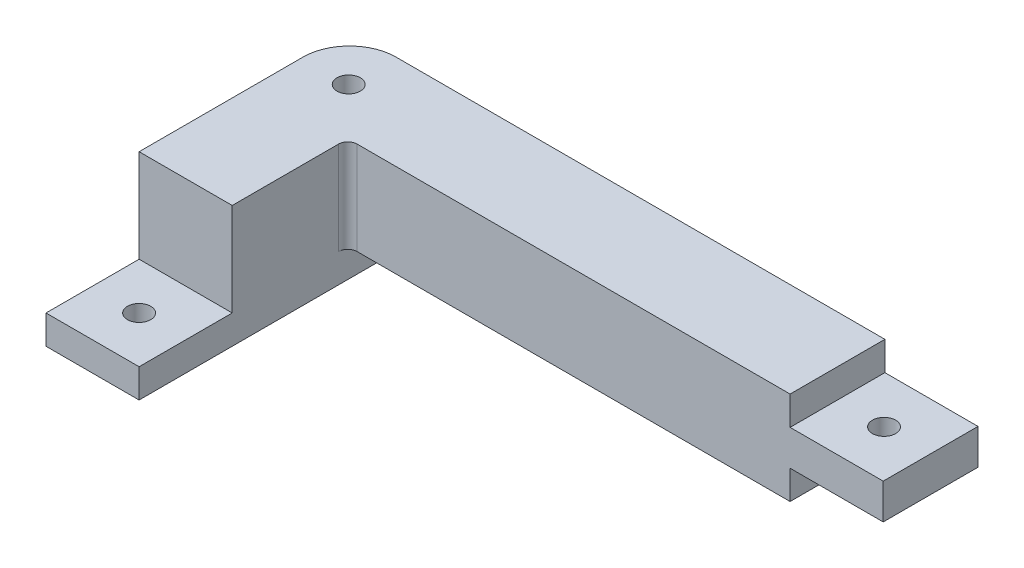
SolidWorks part; units mm, degrees
ref_plane "Front Plane" through (0, 0, 0) normal (0, 0, 1) x (1, 0, 0)
ref_plane "Top Plane" through (0, 0, 0) normal (0, 1, 0) x (1, 0, 0)
ref_plane "Right Plane" through (0, 0, 0) normal (1, 0, 0) x (0, 0, -1)
sketch "Sketch1" plane through (0, 0, 0) normal (0, 1, 0) x (1, 0, 0)
  line L1 (26.3502, -56.9444) -> (0.9502, -56.9444)
  line L2 (26.3502, -56.9444) -> (26.3502, 25.8596)
  line L3 (26.3502, 25.8596) -> (0.9502, 25.8596)
  line L4 (0.9502, -56.9444) -> (0.9502, 25.8596)
  dimension "D1" = 82.804
  dimension "D2" = 25.4
extrude "Boss-Extrude1" add sketch "Sketch1" along normal blind 33.274
sketch "Sketch3" plane through (26.3502, 0, 0) normal (1, 0, 0) x (0, 0, -1)
  line L1 (25.8596, 33.274) -> (0, 33.274)
  line L2 (25.8596, 33.274) -> (25.8596, 7.874)
  line L3 (25.8596, 7.874) -> (0, 7.874)
  line L4 (0, 33.274) -> (0, 7.874)
  dimension "D1" = 25.4
extrude "Boss-Extrude2" add sketch "Sketch3" along normal blind 120.65
sketch "Sketch4" plane through (0, 0, 56.9444) normal (0, 0, 1) x (1, 0, 0)
  line L0 (26.3502, 33.274) -> (26.3502, 0) construction
  line L4 (0.9502, 33.274) -> (26.3502, 33.274)
  line L5 (0.9502, 33.274) -> (0.9502, 7.874)
  line L6 (0.9502, 7.874) -> (26.3502, 7.874)
  line L7 (26.3502, 33.274) -> (26.3502, 7.874)
  dimension "D1" = 25.4
extrude "Cut-Extrude2" cut sketch "Sketch4" against normal blind 25.4
sketch "Sketch5" plane through (147.0002, 0, 0) normal (1, 0, 0) x (0, 0, -1)
  line L0 (0, 15.748) -> (25.8596, 15.748)
  line L1 (0, 33.274) -> (0, 7.874) construction
  line L2 (25.8596, 7.874) -> (25.8596, 33.274) construction
  line L3 (0, 25.4) -> (25.8596, 25.4)
  line L4 (25.8596, 33.274) -> (0, 33.274) construction
  line L5 (0, 25.4) -> (0, 15.748)
  line L6 (25.8596, 25.4) -> (25.8596, 15.748)
  dimension "D1" = 7.874
  dimension "D2" = 9.652
extrude "Boss-Extrude3" add sketch "Sketch5" along normal blind 25.4
sketch "Sketch7" plane through (0, 25.4, 0) normal (0, 1, 0) x (1, 0, 0)
  line L0 (147.0002, 25.8596) -> (172.4002, 0) construction
  circle A0 centre (159.7002, 12.9298) radius 3.175
  dimension "D1" = 6.35
extrude "Cut-Extrude4" cut sketch "Sketch7" against normal blind 41.402
sketch "Sketch8" plane through (0, 7.874, 0) normal (0, 1, 0) x (1, 0, 0)
  line L0 (0.9502, -31.5444) -> (26.3502, -56.9444) construction
  circle A0 centre (13.6502, -44.2444) radius 3.175
  dimension "D1" = 6.35
extrude "Cut-Extrude5" cut sketch "Sketch8" against normal blind 25.4
sketch "Sketch6" plane through (0, 33.274, 0) normal (0, 1, 0) x (1, 0, 0)
  line L1 (159.7002, 12.9298) -> (0.9502, 12.9298) construction
  line L3 (0.9502, 25.8596) -> (0.9502, -31.5444) construction
  line L4 (13.6502, -44.2444) -> (13.6502, 25.8596) construction
  line L5 (147.0002, 25.8596) -> (0.9502, 25.8596) construction
  circle A1 centre (13.6502, 12.9298) radius 3.175
  dimension "D1" = 6.35
extrude "Cut-Extrude3" cut sketch "Sketch6" against normal blind 41.402
fillet "Fillet1" radius 12.7 1 edges at (0.9502, 16.637, -25.8596)
fillet "Fillet2" radius 2.54 1 edges at (26.3502, 20.574, 0)
